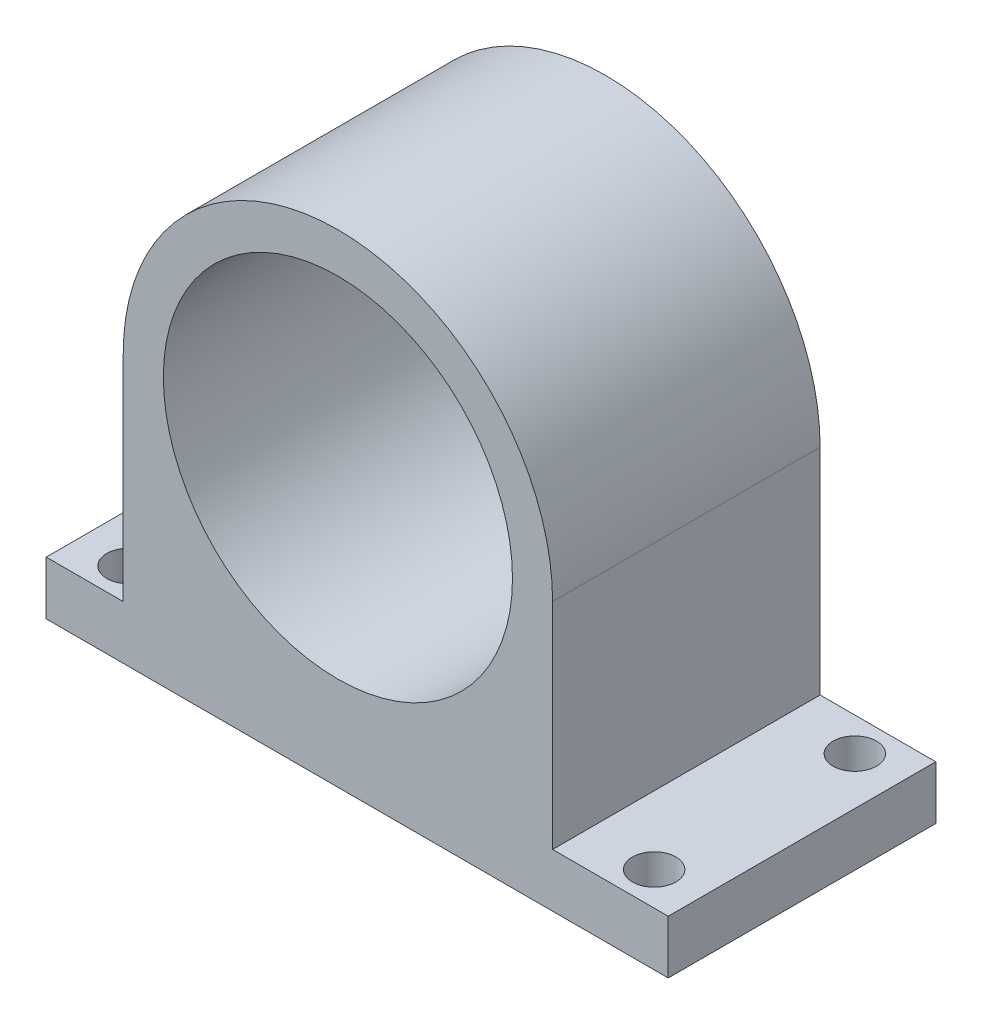
SolidWorks part; units mm, degrees
ref_plane "前视" through (0, 0, 0) normal (0, 0, 1) x (1, 0, 0)
ref_plane "上视" through (0, 0, 0) normal (0, 1, 0) x (1, 0, 0)
ref_plane "右视" through (0, 0, 0) normal (1, 0, 0) x (0, 0, -1)
sketch "草图1" plane through (0, 0, 0) normal (0, 0, 1) x (1, 0, 0)
  line L0 (-32.1, 0) -> (-32.1, -32.1)
  line L1 (-43.6114, -32.1) -> (-32.1, -32.1)
  line L2 (-43.6114, -32.1) -> (-43.6114, -40.1)
  line L3 (-43.6114, -40.1) -> (49.3886, -40.1)
  line L4 (49.3886, -32.1) -> (49.3886, -40.1)
  line L5 (32.1, 0) -> (32.1, -32.1)
  line L6 (32.1, -32.1) -> (49.3886, -32.1)
  circle A0 centre (0, 0) radius 26.1
  arc A1 (32.1, 0) -> (-32.1, 0) centre (0, 0) ccw
  dimension "D3" = 52.2
  dimension "D1" = 93
  dimension "D2" = 8
  dimension "D4" = 32.1
extrude "凸台-拉伸1" add sketch "草图1" along normal blind 40
hole_wizard "Ø6.5 (6.5) 直径孔1" positions "草图3" profile "草图2" hole size "Ø6.5" standard "Gb" end condition through all
sketch "草图3" plane through (0, -32.1, 0) normal (0, 1, 0) x (1, 0, 0)
  line L1 (-43.6114, -40) -> (49.3886, -40) construction
  point P1 (42.2852, -5)
  point P3 (42.2852, -35)
  point P5 (-36.3148, -35)
  point P7 (-36.3148, -5)
  dimension "D1" = 30
  dimension "D3" = 5
  dimension "D5" = 78.6
sketch "草图2" plane through (42.2852, -32.1, 5) normal (1, 0, 0) x (0, 0, 1)
  line L0 (0, 0) -> (0, 8)
  line L1 (0, 8) -> (3.25, 8)
  line L2 (3.25, 8) -> (3.25, 0)
  line L5 (3.25, 0) -> (0, 0)
  line L11 (0, -6.35) -> (0, 107.95) construction
  dimension "通孔孔直径" = 6.5
  dimension "通孔孔深度" = 8
